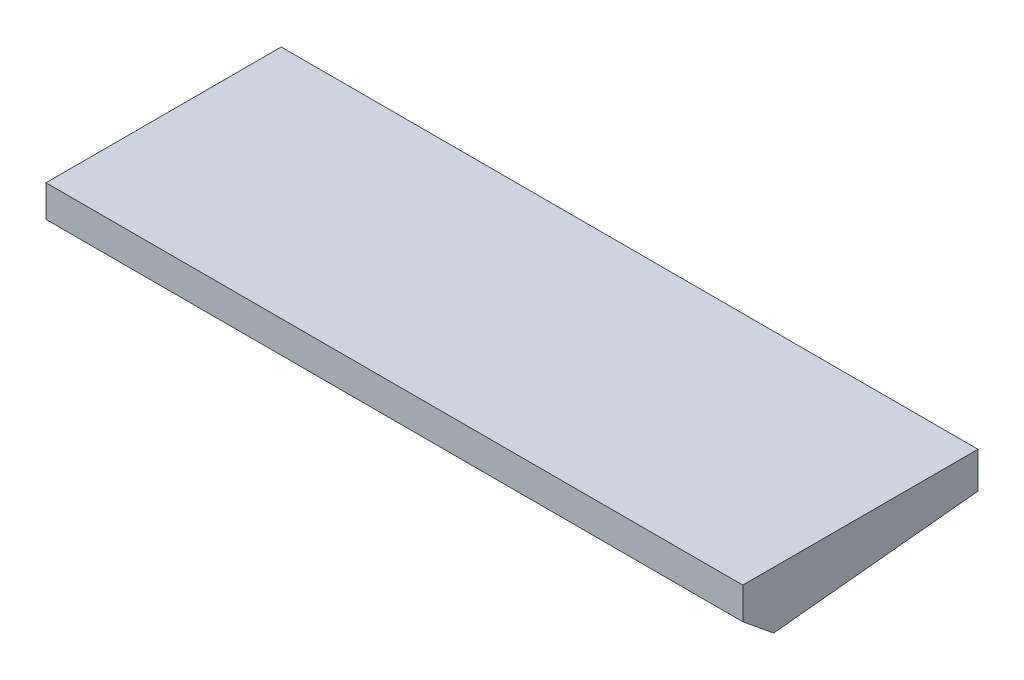
SolidWorks part; units mm, degrees
ref_plane "Front Plane" through (0, 0, 0) normal (0, 0, 1) x (1, 0, 0)
ref_plane "Top Plane" through (0, 0, 0) normal (0, 1, 0) x (1, 0, 0)
ref_plane "Right Plane" through (0, 0, 0) normal (1, 0, 0) x (0, 0, -1)
sketch "Sketch2" plane through (0, 0, 0) normal (1, 0, 0) x (0, 0, -1)
  line L0 (-131.7, 14.1034) -> (-114.4131, 0)
  line L1 (0, 0) -> (-131.7, 0)
  line L2 (0, 0) -> (0, 31.9034)
  line L3 (0, 31.9034) -> (-131.7, 31.9034)
  line L4 (-131.7, 0) -> (-131.7, 31.9034)
  line L5 (-114.4131, 0) -> (0, 11.6034)
  dimension "D1" = 131.7
  dimension "D2" = 115
  dimension "D3" = 17.8
  dimension "D4" = 20.3
  dimension "D5" = 135
extrude "Boss-Extrude1" add sketch "Sketch2" along normal blind 390.2 contours L0 L5 L2 L3 L4
